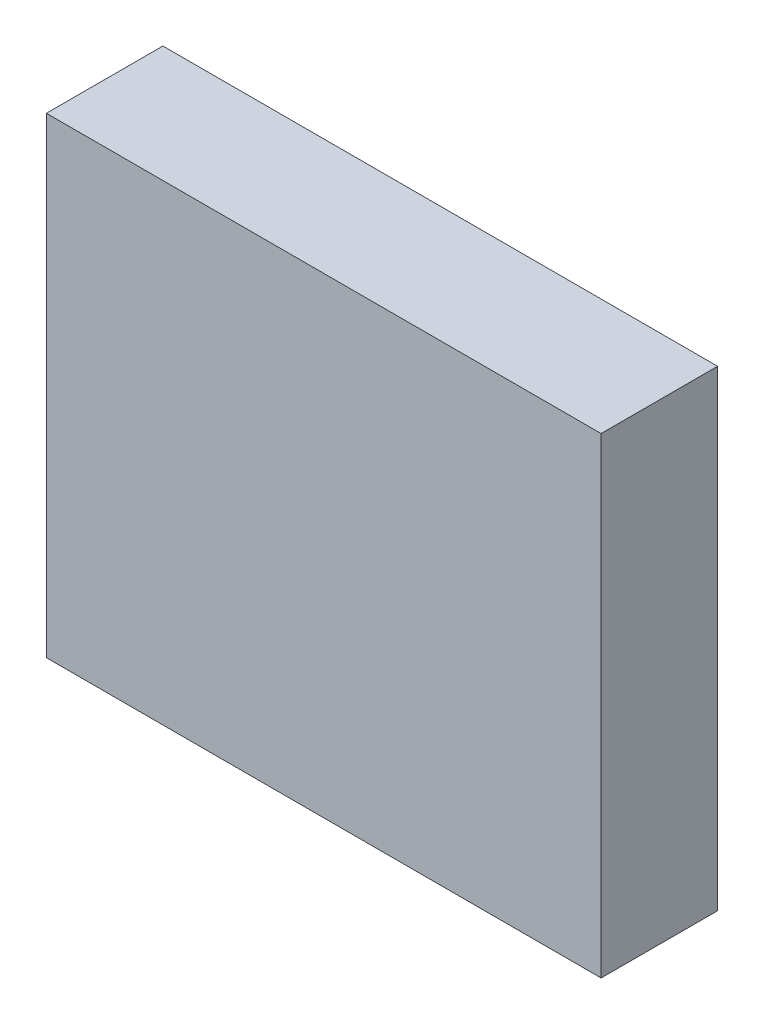
SolidWorks part; units mm, degrees
ref_plane "Front Plane" through (0, 0, 0) normal (0, 0, 1) x (1, 0, 0)
ref_plane "Top Plane" through (0, 0, 0) normal (0, 1, 0) x (1, 0, 0)
ref_plane "Right Plane" through (0, 0, 0) normal (1, 0, 0) x (0, 0, -1)
sketch "Sketch1" plane through (0, 0, 0) normal (0, 0, 1) x (1, 0, 0)
  line L1 (0, 0) -> (25.4, 0)
  line L2 (0, 0) -> (0, -21.59)
  line L3 (0, -21.59) -> (25.4, -21.59)
  line L4 (25.4, 0) -> (25.4, -21.59)
  dimension "D1" = 25.4
  dimension "D2" = 21.59
extrude "Boss-Extrude1" add sketch "Sketch1" along normal blind 5.334
